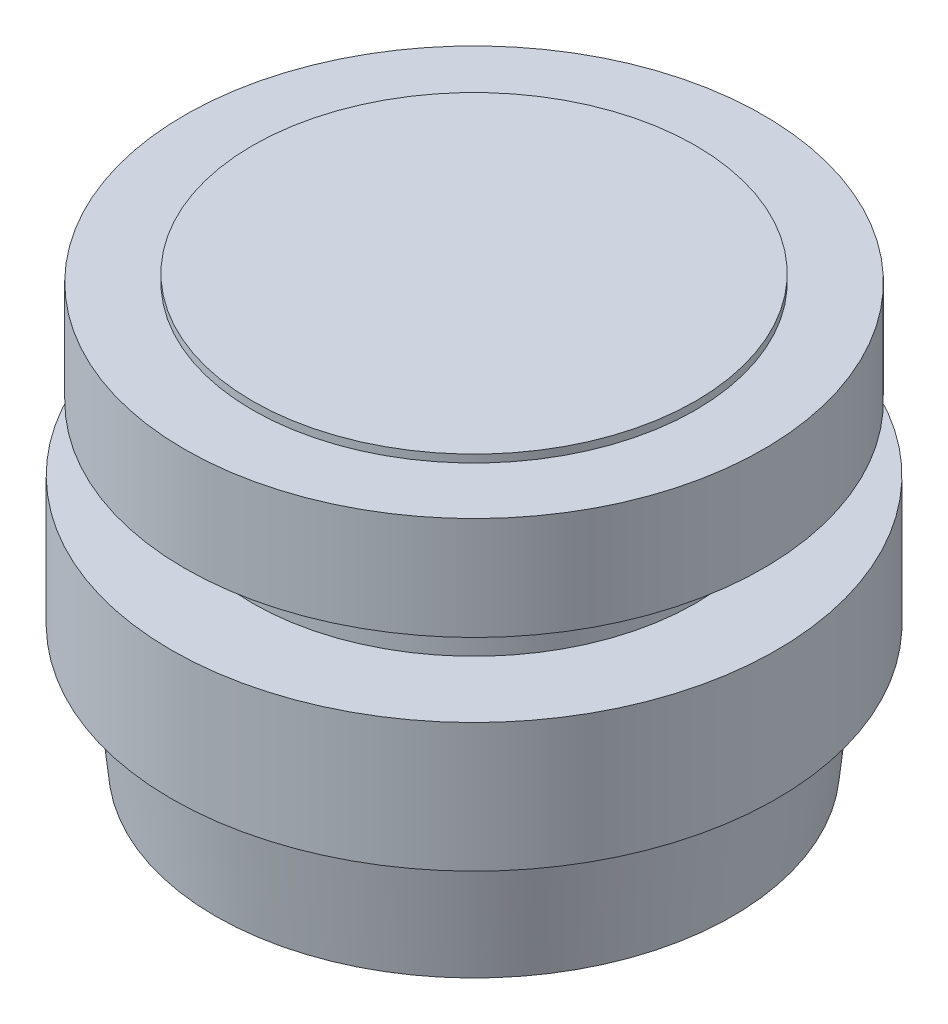
SolidWorks part; units mm, degrees
ref_plane "Front Plane" through (0, 0, 0) normal (0, 0, 1) x (1, 0, 0)
ref_plane "Top Plane" through (0, 0, 0) normal (0, 1, 0) x (1, 0, 0)
ref_plane "Right Plane" through (0, 0, 0) normal (1, 0, 0) x (0, 0, -1)
ref_plane "Plane1" through (0, 0, 0) normal (0, 1, 0) x (1, 0, 0)
sketch "Sketch1" plane through (0, 0, 0) normal (0, 1, 0) x (1, 0, 0)
  circle A0 centre (0, 0) radius 14.9225
extrude "Extrude1" add sketch "Sketch1" along normal blind 6.35
ref_plane "Plane2" through (0, 0, 0) normal (1, 0, 0) x (0, -1, 0)
ref_plane "Plane3" through (0, -2.921, 0) normal (0, 1, 0) x (0, 0, -1)
sketch "Sketch3" plane through (0, -2.921, 0) normal (0, 1, 0) x (0, 0, -1)
  circle A0 centre (0, 0) radius 11.049
extrude "Extrude2" add sketch "Sketch3" along normal up to surface (9.271 mm away) up to face at (0, 6.35, 14.9225)
ref_plane "Plane4" through (0, 0, 0) normal (1, 0, 0) x (0, 0, 1)
sketch "Sketch4" plane through (0, 0, 0) normal (1, 0, 0) x (0, 0, 1)
  line L0 (-11.049, 2.921) -> (-14.3369, -1.1716)
  line L1 (-14.3369, -1.1716) -> (-11.049, -1.1716)
  line L2 (-11.049, -1.1716) -> (-11.049, 2.921)
  line L3 (0, -1.3762) -> (0, 3.1256) construction
revolve "Revolve1" add sketch "Sketch4" angle 360 about L3
sketch "Sketch5" plane through (0, 6.35, 0) normal (0, 1, 0) x (-1, 0, 0)
  circle A0 centre (0, 0) radius 10.922
extrude "Extrude3" add sketch "Sketch5" along normal blind 8.636
ref_plane "Plane5" through (0, 9.525, 0) normal (0, 1, 0) x (0, 0, 1)
sketch "Sketch6" plane through (0, 9.525, 0) normal (0, 1, 0) x (0, 0, 1)
  circle A0 centre (0, 0) radius 14.2763
extrude "Extrude4" add sketch "Sketch6" along normal blind 5.08
sketch "Sketch7" plane through (0, 0, 0) normal (0, -1, 0) x (1, 0, 0)
  circle A0 centre (0, 0) radius 13.3956
  circle A1 centre (0, 0) radius 11.049
extrude "Extrude5" add sketch "Sketch7" along normal offset from surface 3.175 draft 6
